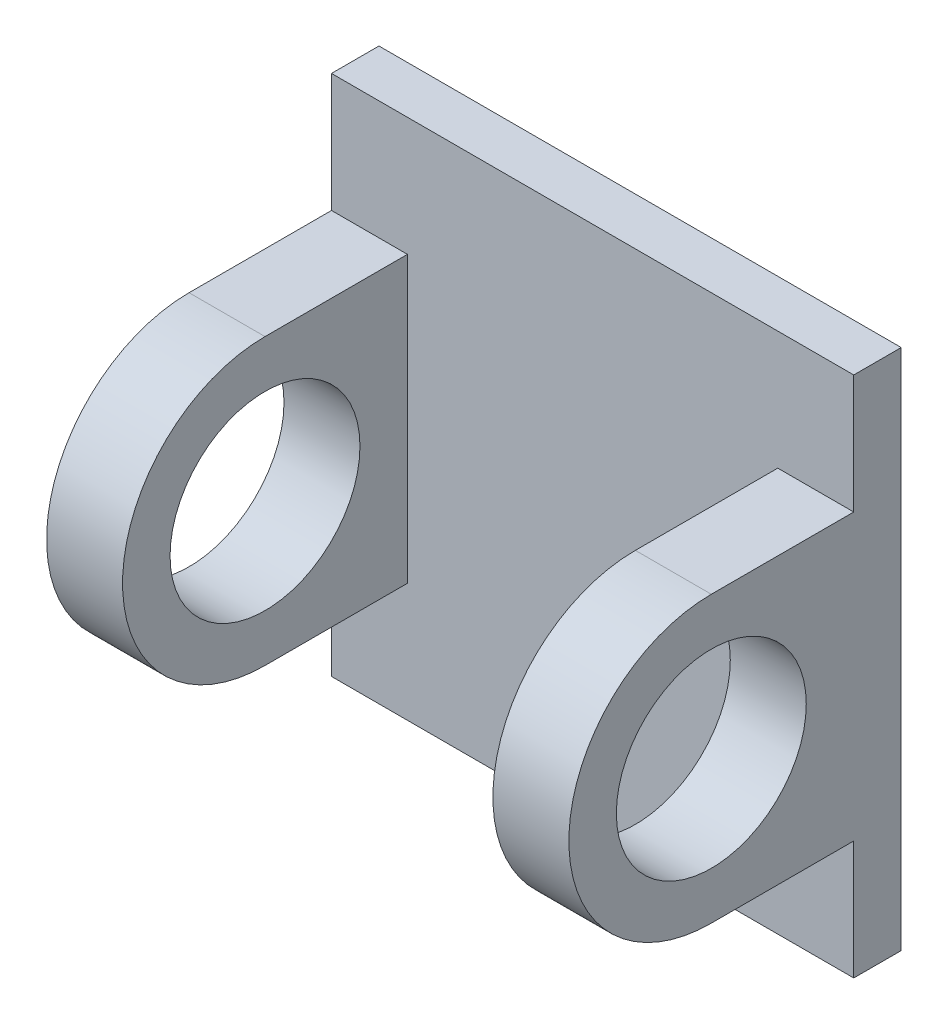
SolidWorks part; units mm, degrees
material "PLA"
ref_plane "Front Plane" through (0, 0, 0) normal (1, 0, 0) x (0, 1, 0)
ref_plane "Top Plane" through (0, 0, 0) normal (0, 0, 1) x (0, 1, 0)
ref_plane "Right Plane" through (0, 0, 0) normal (0, 1, 0) x (-1, 0, 0)
sketch "Sketch1" plane through (0, 0, 0) normal (0, 0, 1) x (0, 1, 0)
  line L1 (-13.75, -13.75) -> (13.75, -13.75)
  line L2 (-13.75, -13.75) -> (-13.75, 13.75)
  line L3 (-13.75, 13.75) -> (13.75, 13.75)
  line L4 (13.75, -13.75) -> (13.75, 13.75)
  line L5 (-13.75, -13.75) -> (13.75, 13.75) construction
  line L6 (-13.75, 13.75) -> (13.75, -13.75) construction
  point P0 (0, 0)
  dimension "D1" = 27.5
extrude "Boss-Extrude1" add sketch "Sketch1" along normal blind 2.5
sketch "Sketch2" plane through (13.75, 0, 0) normal (1, 0, 0) x (0, 1, 0)
  line L0 (-7.5, 2.5) -> (7.5, 2.5)
  line L1 (-13.75, 2.5) -> (13.75, 2.5) construction
  line L2 (7.5, 2.5) -> (7.5, 10)
  line L3 (-7.5, 2.5) -> (-7.5, 10)
  arc A0 (7.5, 10) -> (-7.5, 10) centre (0, 10) ccw
  circle A1 centre (0, 10) radius 5
  point P5 (0, 2.5)
  dimension "D1" = 10
  dimension "D2" = 2.5
  dimension "D3" = 7.5
extrude "Boss-Extrude2" add sketch "Sketch2" against normal blind 27.5
sketch "Sketch3" plane through (0, 0, 0) normal (1, 0, 0) x (0, 1, 0)
  line L1 (-13.75, 2.5) -> (13.75, 2.5)
  line L2 (-13.75, 2.5) -> (-13.75, 18.2629)
  line L3 (-13.75, 18.2629) -> (13.75, 18.2629)
  line L4 (13.75, 2.5) -> (13.75, 18.2629)
extrude "Cut-Extrude1" cut sketch "Sketch3" against normal offset from surface 4 and the other way offset from surface (9.75 mm away) 4 up to face at (-13.75, 0, 4.6875) other way up to face at (13.75, 0, 4.6875)
sketch "Sketch4" plane through (0, 13.75, 0) normal (0, 1, 0) x (-1, 0, 0)
  line L1 (-13.75, 0) -> (13.75, 0)
  line L2 (-13.75, 0) -> (-13.75, 2.5)
  line L3 (-13.75, 2.5) -> (13.75, 2.5)
  line L4 (13.75, 0) -> (13.75, 2.5)
extrude "Cut-Extrude2" [suppressed] cut sketch "Sketch4" against normal up to surface (7.0945 mm away)
sketch "Sketch5" plane through (0, -13.75, 0) normal (0, -1, 0) x (1, 0, 0)
  line L1 (-13.75, 0) -> (13.75, 0)
  line L2 (-13.75, 0) -> (-13.75, 2.5)
  line L3 (-13.75, 2.5) -> (13.75, 2.5)
  line L4 (13.75, 0) -> (13.75, 2.5)
extrude "Cut-Extrude3" [suppressed] cut sketch "Sketch5" against normal up to surface (5.4055 mm away)
equation "\"ball_diameter\"= 0.75in"
equation "\"wall_thickness\" = 0.25cm"
equation "\"track_length\" = 25cm"
equation "\"axle\" = 5mm"
equation "\"pillar_width\" = 2.75cm"
equation "\"D1@Sketch1\"=\"pillar_width\""
equation "\"D1@Boss-Extrude1\"=\"wall_thickness\""
